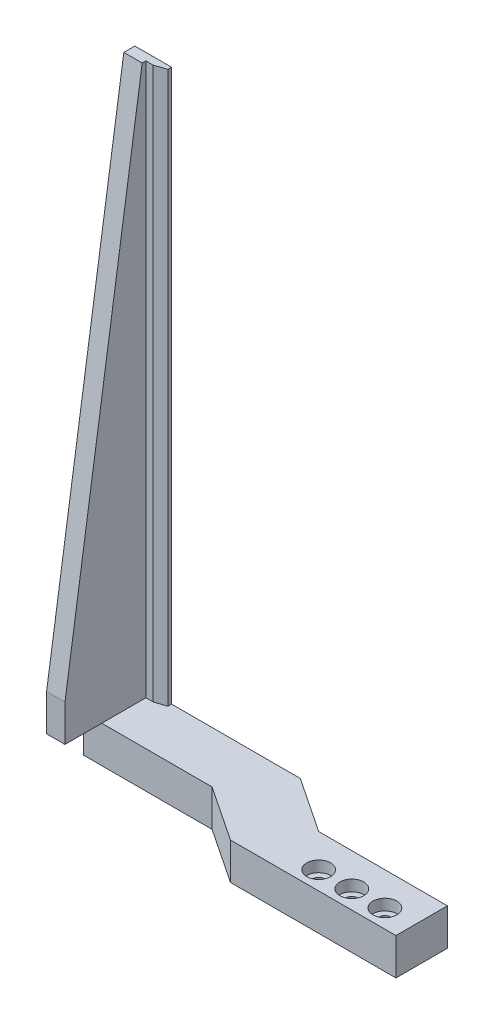
SolidWorks part; units mm, degrees
ref_plane "Ebene vorne" through (0, 0, 0) normal (0, 0, 1) x (1, 0, 0)
ref_plane "Ebene oben" through (0, 0, 0) normal (0, 1, 0) x (1, 0, 0)
ref_plane "Ebene rechts" through (0, 0, 0) normal (1, 0, 0) x (0, 0, -1)
sketch "Skizze1" plane through (0, 0, 0) normal (0, 0, 1) x (1, 0, 0)
  line L0 (-10, 10) -> (-95, 10)
  line L1 (-95, 10) -> (-95, 160)
  line L2 (-95, 160) -> (-105, 160)
  line L3 (-105, 160) -> (-105, 0)
  line L4 (-105, 0) -> (-10, 0)
  line L5 (-10, 0) -> (-10, 10)
  line L6 (0, 0) -> (0, 115.6222) construction
  dimension "D1" = 190
  dimension "D2" = 10
  dimension "D3" = 10
  dimension "D4" = 150
  dimension "D5" = 10
extrude "Aufsatz-Linear austragen1" add sketch "Skizze1" along normal blind 2
sketch "Skizze2" plane through (0, 0, 2) normal (0, 0, 1) x (1, 0, 0)
  line L0 (-105, 0) -> (-10, 0) construction
  line L1 (-105, 160) -> (-105, 0) construction
  line L2 (-105, 0) -> (-10, 0)
  line L3 (-105, 160) -> (-105, 0)
  line L4 (-105, 160) -> (-100, 160)
  line L5 (-95, 160) -> (-105, 160) construction
  line L6 (-100, 160) -> (-100, 10)
  line L7 (-100, 10) -> (-10, 10)
  line L8 (-10, 0) -> (-10, 10) construction
  line L9 (-10, 10) -> (-10, 0)
  dimension "D1" = 5
  dimension "D2" = 10
extrude "Aufsatz-Linear austragen2" add sketch "Skizze2" along normal blind 22
sketch "Skizze3" plane through (-105, 0, 0) normal (-1, 0, 0) x (0, 0, 1)
  line L5 (3, 160) -> (24, 160)
  line L7 (24, 160) -> (24, 20)
  line L9 (24, 20) -> (3, 160)
  line L10 (24, 160) -> (0, 160) construction
  line L12 (24, 160) -> (24, 0) construction
  line L13 (24, 0) -> (0, 0) construction
  line L14 (0, 160) -> (0, 0) construction
  dimension "D1" = 20
  dimension "D2" = 3
extrude "Schnitt-Linear austragen1" cut sketch "Skizze3" against normal up to next
chamfer "Fase1" distance 1 distance2 3 3 edges at (-95, 85, 2) (-97.5, 10, 2) (-95, 10, 1)
sketch "Skizze4" plane through (0, 10, 0) normal (0, 1, 0) x (1, 0, 0)
  line L1 (-47.9352, -19) -> (-9.3438, -19) construction
  line L2 (0, 0) -> (0, -47.6851) construction
  line L3 (-10, -24) -> (-100, -24) construction
  circle A0 centre (-18, -19) radius 1.7
  circle A1 centre (-27, -19) radius 1.7
  circle A2 centre (-36, -19) radius 1.7
  dimension "D1" = 3.4
  dimension "D5" = 5
  dimension "D2" = 9
  dimension "D3" = 9
  dimension "D4" = 18
extrude "Schnitt-Linear austragen2" cut sketch "Skizze4" against normal up to next
sketch "Skizze5" plane through (0, 10, 0) normal (0, 1, 0) x (1, 0, 0)
  circle A0 centre (-18, -19) radius 3.25
  circle A1 centre (-27, -19) radius 3.25
  circle A2 centre (-36, -19) radius 3.25
  point P9 (-36, -6)
  dimension "D1" = 6.5
extrude "Schnitt-Linear austragen3" cut sketch "Skizze5" against normal blind 3
sketch "Skizze6" plane through (0, 10, 0) normal (0, 1, 0) x (1, 0, 0)
  line L0 (-10, -10) -> (-10, 0)
  line L1 (-10, -24) -> (-10, 0) construction
  line L2 (-10, 0) -> (-60, 0)
  line L3 (-10, 0) -> (-95, 0) construction
  line L6 (-10, -10) -> (-45, -10)
  line L7 (-45, -10) -> (-60, 0)
  line L8 (-55, -24) -> (-70, -14)
  line L9 (-10, -24) -> (-100, -24) construction
  line L10 (-70, -14) -> (-105, -14)
  line L11 (-105, -3) -> (-105, -24) construction
  line L12 (-105, -14) -> (-105, -24)
  line L13 (-105, -24) -> (-55, -24)
  dimension "D1" = 10
  dimension "D2" = 50
  dimension "D3" = 35
  dimension "D4" = 50
  dimension "D5" = 10
extrude "Schnitt-Linear austragen4" cut sketch "Skizze6" against normal up to next
